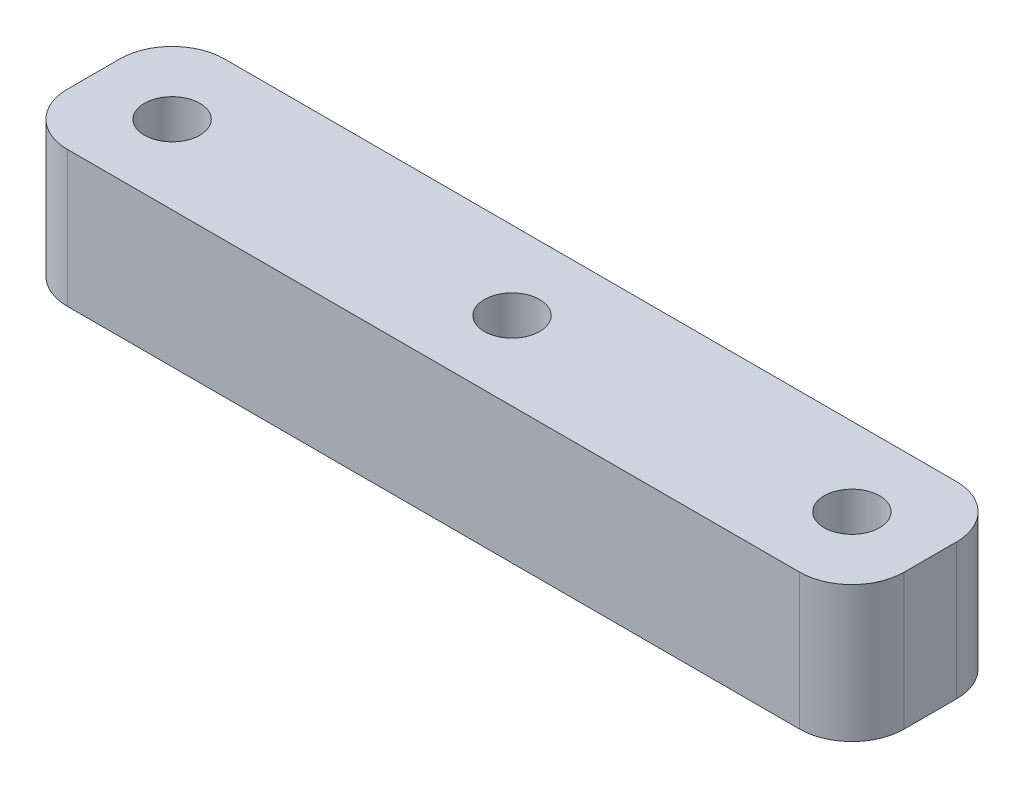
SolidWorks part; units mm, degrees
material "ABS"
ref_plane "Front Plane" through (0, 0, 0) normal (0, 0, 1) x (1, 0, 0)
ref_plane "Top Plane" through (0, 0, 0) normal (0, 1, 0) x (1, 0, 0)
ref_plane "Right Plane" through (0, 0, 0) normal (1, 0, 0) x (0, 0, -1)
sketch "Sketch1" plane through (0, 0, 0) normal (0, 1, 0) x (1, 0, 0)
  line L0 (-32.5, 0) -> (32.5, 0) construction
  line L1 (-40, 7.5) -> (40, 7.5)
  line L2 (-40, 7.5) -> (-40, -7.5)
  line L3 (-40, -7.5) -> (40, -7.5)
  line L4 (40, 7.5) -> (40, -7.5)
  circle A0 centre (0, 0) radius 2.5 construction
  circle A1 centre (32.5, 0) radius 2.5 construction
  circle A2 centre (-32.5, 0) radius 2.5 construction
  point P11 (0, 7.5)
  point P13 (-40, 0)
  dimension "D3" = 5
  dimension "D1" = 65
  dimension "D2" = 80
  dimension "D4" = 15
extrude "Boss-Extrude1" add sketch "Sketch1" against normal blind 13
hole_wizard "M5 Clearance Hole1" positions "3DSketch1" profile "Sketch2" hole size "M5" standard "ANSI Metric" end condition up to next
sketch3d "3DSketch1"
  point P0 (-32.5, 0, 0)
  point P2 (0, 0, 0)
  point P4 (32.5, 0, 0)
sketch "Sketch2" plane through (-32.5, 0, 0) normal (1, 0, 0) x (0, 0, 1)
  line L0 (0, 0) -> (0, 13)
  line L1 (0, 13) -> (2.65, 13)
  line L2 (2.65, 13) -> (2.65, 0)
  line L5 (2.65, 0) -> (0, 0)
  line L11 (0, -6.35) -> (0, 107.95) construction
  dimension "Thru Hole Dia." = 5.3
  dimension "Thru Hole Depth" = 13
fillet "Fillet1" radius 5 4 edges at (-40, -6.5, -7.5) (40, -6.5, -7.5) (40, -6.5, 7.5) (-40, -6.5, 7.5)
